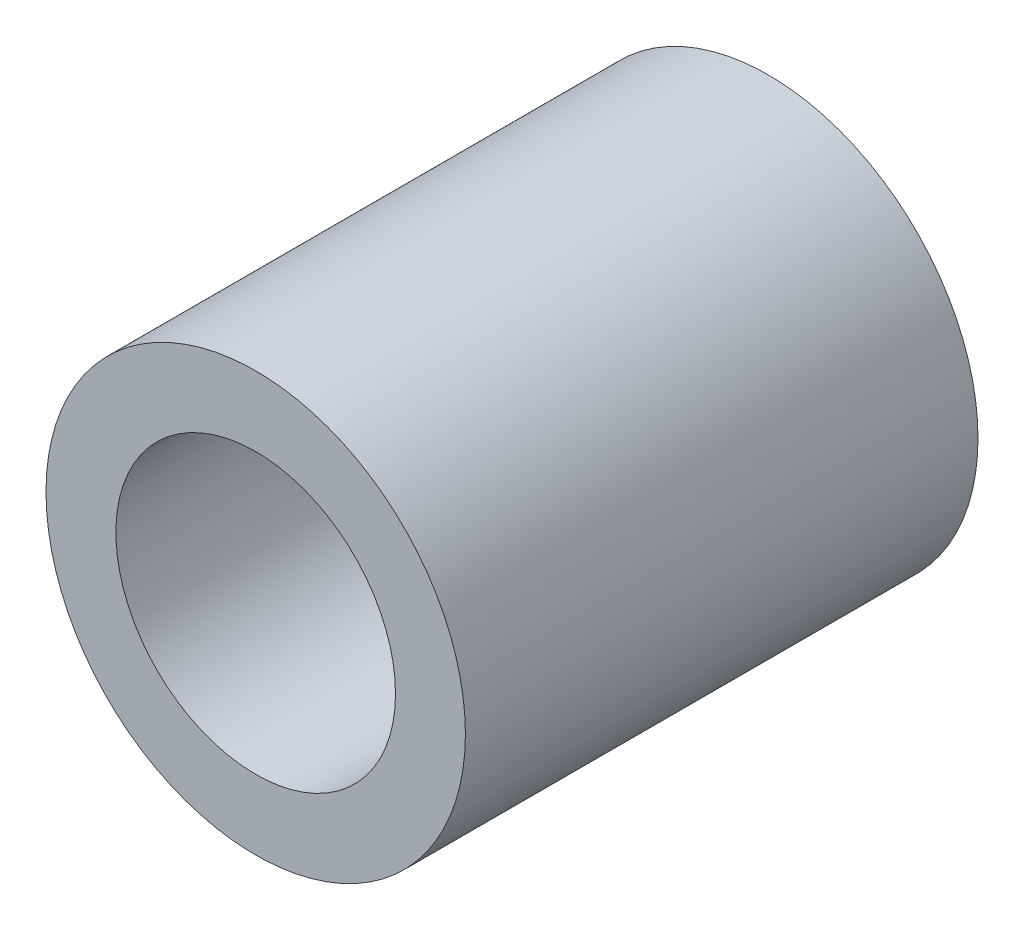
SolidWorks part; units mm, degrees
ref_plane "Płaszczyzna przednia" through (0, 0, 0) normal (0, 0, 1) x (1, 0, 0)
ref_plane "Płaszczyzna górna" through (0, 0, 0) normal (0, 1, 0) x (1, 0, 0)
ref_plane "Płaszczyzna prawa" through (0, 0, 0) normal (1, 0, 0) x (0, 0, -1)
sketch "Sketch1" plane through (0, 0, 0) normal (0, 0, 1) x (1, 0, 0)
  circle A0 centre (0, 0) radius 6
  circle A1 centre (0, 0) radius 9
  dimension "D1" = 3
  dimension "D2" = 12
extrude "Boss-Extrude1" add sketch "Sketch1" along normal mid plane 22
